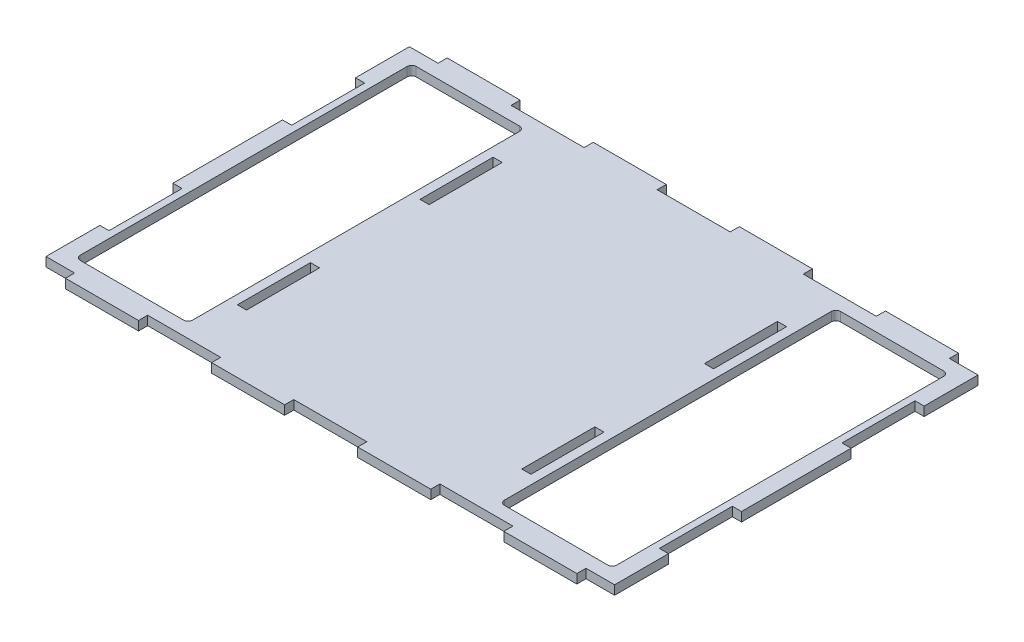
SolidWorks part; units mm, degrees
material "Acrylic (Medium-high impact)"
ref_plane "Front Plane" through (0, 0, 0) normal (0, 0, 1) x (1, 0, 0)
ref_plane "Top Plane" through (0, 0, 0) normal (0, 1, 0) x (1, 0, 0)
ref_plane "Right Plane" through (0, 0, 0) normal (1, 0, 0) x (0, 0, -1)
sketch "Sketch2" plane through (0, 0, 0) normal (0, 1, 0) x (1, 0, 0)
  line L0 (-147.5, 0) -> (147.5, 0) construction
  line L5 (-185, 195.2) -> (185, 195.2) construction
  line L6 (-197.7, -132.7) -> (197.7, -132.7)
  line L13 (110, 120) -> (185, 120)
  line L14 (110, 120) -> (110, -120)
  line L15 (110, -120) -> (185, -120)
  line L16 (185, 120) -> (185, -120)
  line L17 (110, 120) -> (185, -120) construction
  line L18 (110, -120) -> (185, 120) construction
  line L19 (-185, 120) -> (-110, 120)
  line L20 (-185, 120) -> (-185, -120)
  line L21 (-185, -120) -> (-110, -120)
  line L22 (-110, 120) -> (-110, -120)
  line L23 (-185, 120) -> (-110, -120) construction
  line L24 (-185, -120) -> (-110, 120) construction
  line L26 (-110, -37.5) -> (110, -37.5)
  line L27 (-110, -37.5) -> (-110, 37.5)
  line L28 (-110, 37.5) -> (110, 37.5)
  line L29 (110, -37.5) -> (110, 37.5)
  line L30 (-110, -37.5) -> (110, 37.5) construction
  line L31 (-110, 37.5) -> (110, -37.5) construction
  line L41 (-197.7, -132.7) -> (-197.7, 132.7)
  line L42 (-185, 132.7) -> (185, 132.7) construction
  line L43 (197.7, -132.7) -> (197.7, 132.7)
  line L44 (-197.7, -132.7) -> (197.7, 132.7) construction
  line L45 (-197.7, 132.7) -> (197.7, -132.7) construction
  line L47 (-197.7, 132.7) -> (-197.7, 257.7)
  line L48 (-197.7, 257.7) -> (-185, 257.7)
  line L49 (-185, 132.7) -> (-185, 257.7)
  line L51 (185, 132.7) -> (185, 257.7)
  line L52 (185, 257.7) -> (197.7, 257.7)
  line L53 (197.7, 132.7) -> (197.7, 257.7)
  line L54 (-185, 132.7) -> (185, 132.7)
  line L55 (223.1, 132.7) -> (223.1, 283.1)
  line L56 (159.6, 283.1) -> (223.1, 283.1)
  line L57 (159.6, 158.1) -> (159.6, 283.1)
  line L58 (-159.6, 158.1) -> (159.6, 158.1)
  line L59 (-159.6, 158.1) -> (-159.6, 283.1)
  line L60 (-223.1, 283.1) -> (-159.6, 283.1)
  line L61 (-223.1, 132.7) -> (-223.1, 283.1)
  line L62 (-223.1, -158.1) -> (-223.1, 132.7)
  line L63 (-223.1, -158.1) -> (223.1, -158.1)
  line L64 (223.1, -158.1) -> (223.1, 132.7)
  circle A0 centre (0, 308.1) radius 150
  point P2 (0, 0)
  point P13 (147.5, 0)
  point P18 (-147.5, 0)
  point P23 (0, 0)
  point P24 (0, 0)
  point P35 (0, 195.2)
  dimension "D1" = 300
  dimension "D2" = 75
  dimension "D3" = 240
  dimension "D4" = 75
  dimension "D5" = 220
  dimension "D6" = 12.7
  dimension "D7" = 12.7
  dimension "D8" = 12.7
  dimension "D9" = 125
  dimension "D10" = 25.4
sketch "Sketch5" plane through (0, 0, 0) normal (0, 1, 0) x (1, 0, 0)
  line L1 (197.7, -132.7) -> (-197.7, -132.7)
  line L2 (197.7, -132.7) -> (197.7, 132.7)
  line L3 (197.7, 132.7) -> (-197.7, 132.7)
  line L4 (-197.7, -132.7) -> (-197.7, 132.7)
extrude "Boss-Extrude3" add sketch "Sketch5" along normal blind 6.35
sketch "Sketch6" plane through (0, 6.35, 0) normal (0, 1, 0) x (1, 0, 0)
  line L0 (-185, 120) -> (-110, 120) construction
  line L1 (-185, 120) -> (-185, -120) construction
  line L2 (-185, -120) -> (-110, -120) construction
  line L3 (-110, 120) -> (-110, -120) construction
  line L4 (110, 120) -> (110, -120) construction
  line L5 (110, 120) -> (185, 120) construction
  line L6 (185, 120) -> (185, -120) construction
  line L7 (110, -120) -> (185, -120) construction
  line L8 (-185, 120) -> (-110, 120)
  line L9 (-185, 120) -> (-185, -120)
  line L10 (-185, -120) -> (-110, -120)
  line L11 (-110, 120) -> (-110, -120)
  line L12 (110, 120) -> (110, -120)
  line L13 (110, 120) -> (185, 120)
  line L14 (185, 120) -> (185, -120)
  line L15 (110, -120) -> (185, -120)
  line L16 (108.4125, 121.5875) -> (108.4125, -121.5875)
  line L17 (108.4125, -121.5875) -> (186.5875, -121.5875)
  line L18 (186.5875, 121.5875) -> (186.5875, -121.5875)
  line L19 (108.4125, 121.5875) -> (186.5875, 121.5875)
  line L20 (-108.4125, 121.5875) -> (-108.4125, -121.5875)
  line L21 (-186.5875, -121.5875) -> (-108.4125, -121.5875)
  line L22 (-186.5875, 121.5875) -> (-186.5875, -121.5875)
  line L23 (-186.5875, 121.5875) -> (-108.4125, 121.5875)
  dimension "D1" = 1.5875
extrude "Cut-Extrude1" cut sketch "Sketch6" against normal blind 6.35 contours L12 L15 L14 L13 | L19 L16 L17 L18 L15 L12 L13 L14 | L11 L8 L9 L10 | L23 L22 L21 L20 L8 L11 L10 L9
sketch "Sketch7" [suppressed] plane through (0, 6.35, 0) normal (0, 1, 0) x (1, 0, 0)
  arc A0 (191.675, -14.35) -> (191.043, -17.5242) centre (191.675, -16) ccw construction
  arc A1 (192.307, -14.4758) -> (191.675, -14.35) centre (191.675, -16) ccw construction
  arc A2 (191.675, -17.65) -> (192.307, -14.4758) centre (191.675, -16) ccw construction
  arc A3 (191.043, -17.5242) -> (191.675, -17.65) centre (191.675, -16) ccw construction
  arc A4 (191.675, 17.65) -> (191.043, 14.4758) centre (191.675, 16) ccw construction
  arc A5 (192.307, 17.5242) -> (191.675, 17.65) centre (191.675, 16) ccw construction
  arc A6 (191.675, 14.35) -> (192.307, 17.5242) centre (191.675, 16) ccw construction
  arc A7 (191.043, 14.4758) -> (191.675, 14.35) centre (191.675, 16) ccw construction
  arc A8 (103.325, -14.35) -> (102.693, -17.5242) centre (103.325, -16) ccw construction
  arc A9 (103.957, -14.4758) -> (103.325, -14.35) centre (103.325, -16) ccw construction
  arc A10 (103.325, -17.65) -> (103.957, -14.4758) centre (103.325, -16) ccw construction
  arc A11 (102.693, -17.5242) -> (103.325, -17.65) centre (103.325, -16) ccw construction
  arc A12 (103.325, 17.65) -> (102.693, 14.4758) centre (103.325, 16) ccw construction
  arc A13 (103.957, 17.5242) -> (103.325, 17.65) centre (103.325, 16) ccw construction
  arc A14 (103.325, 14.35) -> (103.957, 17.5242) centre (103.325, 16) ccw construction
  arc A15 (102.693, 14.4758) -> (103.325, 14.35) centre (103.325, 16) ccw construction
  arc A16 (-103.325, 17.65) -> (-103.957, 14.4758) centre (-103.325, 16) ccw construction
  arc A17 (-102.693, 17.5242) -> (-103.325, 17.65) centre (-103.325, 16) ccw construction
  arc A18 (-103.325, 14.35) -> (-102.693, 17.5242) centre (-103.325, 16) ccw construction
  arc A19 (-103.957, 14.4758) -> (-103.325, 14.35) centre (-103.325, 16) ccw construction
  arc A20 (-103.325, -14.35) -> (-103.957, -17.5242) centre (-103.325, -16) ccw construction
  arc A21 (-102.693, -14.4758) -> (-103.325, -14.35) centre (-103.325, -16) ccw construction
  arc A22 (-103.325, -17.65) -> (-102.693, -14.4758) centre (-103.325, -16) ccw construction
  arc A23 (-103.957, -17.5242) -> (-103.325, -17.65) centre (-103.325, -16) ccw construction
  arc A24 (-191.675, -14.35) -> (-192.307, -17.5242) centre (-191.675, -16) ccw construction
  arc A25 (-191.043, -14.4758) -> (-191.675, -14.35) centre (-191.675, -16) ccw construction
  arc A26 (-191.675, -17.65) -> (-191.043, -14.4758) centre (-191.675, -16) ccw construction
  arc A27 (-192.307, -17.5242) -> (-191.675, -17.65) centre (-191.675, -16) ccw construction
  arc A28 (-191.675, 14.35) -> (-191.043, 17.5242) centre (-191.675, 16) ccw construction
  arc A29 (-192.307, 14.4758) -> (-191.675, 14.35) centre (-191.675, 16) ccw construction
  arc A30 (-191.675, 17.65) -> (-192.307, 14.4758) centre (-191.675, 16) ccw construction
  arc A31 (-191.043, 17.5242) -> (-191.675, 17.65) centre (-191.675, 16) ccw construction
  circle A32 centre (-61.175, -10) radius 2.25 construction
  circle A33 centre (-61.175, 22) radius 2.25 construction
  circle A34 centre (61.175, 22) radius 2.25 construction
  circle A35 centre (61.175, -10) radius 2.25 construction
  arc A36 (191.675, -14.35) -> (191.043, -17.5242) centre (191.675, -16) ccw construction
  arc A37 (192.307, -14.4758) -> (191.675, -14.35) centre (191.675, -16) ccw construction
  arc A38 (191.675, -17.65) -> (192.307, -14.4758) centre (191.675, -16) ccw construction
  arc A39 (191.043, -17.5242) -> (191.675, -17.65) centre (191.675, -16) ccw construction
  arc A40 (191.675, 17.65) -> (191.043, 14.4758) centre (191.675, 16) ccw construction
  arc A41 (192.307, 17.5242) -> (191.675, 17.65) centre (191.675, 16) ccw construction
  arc A42 (191.675, 14.35) -> (192.307, 17.5242) centre (191.675, 16) ccw construction
  arc A43 (191.043, 14.4758) -> (191.675, 14.35) centre (191.675, 16) ccw construction
  arc A44 (103.325, -14.35) -> (102.693, -17.5242) centre (103.325, -16) ccw construction
  arc A45 (103.957, -14.4758) -> (103.325, -14.35) centre (103.325, -16) ccw construction
  arc A46 (103.325, -17.65) -> (103.957, -14.4758) centre (103.325, -16) ccw construction
  arc A47 (102.693, -17.5242) -> (103.325, -17.65) centre (103.325, -16) ccw construction
  arc A48 (103.325, 17.65) -> (102.693, 14.4758) centre (103.325, 16) ccw construction
  arc A49 (103.957, 17.5242) -> (103.325, 17.65) centre (103.325, 16) ccw construction
  arc A50 (103.325, 14.35) -> (103.957, 17.5242) centre (103.325, 16) ccw construction
  arc A51 (102.693, 14.4758) -> (103.325, 14.35) centre (103.325, 16) ccw construction
  arc A52 (-103.325, 17.65) -> (-103.957, 14.4758) centre (-103.325, 16) ccw construction
  arc A53 (-102.693, 17.5242) -> (-103.325, 17.65) centre (-103.325, 16) ccw construction
  arc A54 (-103.325, 14.35) -> (-102.693, 17.5242) centre (-103.325, 16) ccw construction
  arc A55 (-103.957, 14.4758) -> (-103.325, 14.35) centre (-103.325, 16) ccw construction
  arc A56 (-103.325, -14.35) -> (-103.957, -17.5242) centre (-103.325, -16) ccw construction
  arc A57 (-102.693, -14.4758) -> (-103.325, -14.35) centre (-103.325, -16) ccw construction
  arc A58 (-103.325, -17.65) -> (-102.693, -14.4758) centre (-103.325, -16) ccw construction
  arc A59 (-103.957, -17.5242) -> (-103.325, -17.65) centre (-103.325, -16) ccw construction
  arc A60 (-191.675, -14.35) -> (-192.307, -17.5242) centre (-191.675, -16) ccw construction
  arc A61 (-191.043, -14.4758) -> (-191.675, -14.35) centre (-191.675, -16) ccw construction
  arc A62 (-191.675, -17.65) -> (-191.043, -14.4758) centre (-191.675, -16) ccw construction
  arc A63 (-192.307, -17.5242) -> (-191.675, -17.65) centre (-191.675, -16) ccw construction
  arc A64 (-191.675, 14.35) -> (-191.043, 17.5242) centre (-191.675, 16) ccw construction
  arc A65 (-192.307, 14.4758) -> (-191.675, 14.35) centre (-191.675, 16) ccw construction
  arc A66 (-191.675, 17.65) -> (-192.307, 14.4758) centre (-191.675, 16) ccw construction
  arc A67 (-191.043, 17.5242) -> (-191.675, 17.65) centre (-191.675, 16) ccw construction
  circle A68 centre (-61.175, -10) radius 2.25 construction
  circle A69 centre (-61.175, 22) radius 2.25 construction
  circle A70 centre (61.175, 22) radius 2.25 construction
  circle A71 centre (61.175, -10) radius 2.25 construction
hole_wizard "Ø4.0mm Dowel Hole1" [suppressed] positions "Sketch8" profile "Sketch9" hole size "Ø4.0" standard "ANSI Metric"
sketch "Sketch8" [suppressed] plane through (0, 6.35, 0) normal (0, 1, 0) x (1, 0, 0)
  point P0 (191.675, -16)
  point P3 (191.675, 16)
  point P6 (103.325, -16)
  point P9 (103.325, 16)
  point P12 (-191.675, -16)
  point P15 (-191.675, 16)
  point P18 (-103.325, -16)
  point P21 (-103.325, 16)
  point P24 (-61.175, -10)
  point P27 (-61.175, 22)
  point P30 (61.175, 22)
  point P33 (61.175, -10)
sketch "Sketch9" plane through (191.675, 6.35, 16) normal (1, 0, 0) x (0, 0, 1)
  line L0 (0, 0) -> (0, 6.35)
  line L1 (0, 6.35) -> (2.25, 6.35)
  line L2 (2.25, 6.35) -> (2.25, 0)
  line L5 (2.25, 0) -> (0, 0)
  line L11 (0, -6.35) -> (0, 107.95) construction
  dimension "Thru Hole Dia." = 4.5
  dimension "Thru Hole Depth" = 6.35
sketch "Sketch10" plane through (0, 0, 0) normal (0, -1, 0) x (1, 0, 0)
  line L0 (-191.35, -126.35) -> (191.35, -126.35)
  line L1 (191.35, -126.35) -> (191.35, 126.35)
  line L2 (191.35, 126.35) -> (-191.35, 126.35)
  line L3 (-191.35, 126.35) -> (-191.35, -126.35)
  line L4 (197.7, -132.7) -> (197.7, 132.7)
  line L5 (197.7, 132.7) -> (-197.7, 132.7)
  line L6 (-197.7, 132.7) -> (-197.7, -132.7)
  line L7 (-197.7, -132.7) -> (197.7, -132.7)
  line L8 (197.7, -132.7) -> (197.7, 132.7)
  line L9 (197.7, 132.7) -> (-197.7, 132.7)
  line L10 (-197.7, 132.7) -> (-197.7, -132.7)
  line L11 (-197.7, -132.7) -> (197.7, -132.7)
  line L12 (102.0625, -126.35) -> (102.0625, 126.35)
  line L13 (-102.0625, -126.35) -> (-102.0625, 126.35)
  line L14 (108.4125, -126.35) -> (108.4125, 126.35)
  line L15 (-108.4125, -126.35) -> (-108.4125, 126.35)
  line L16 (108.4125, -121.5875) -> (108.4125, 121.5875) construction
  line L17 (-108.4125, -121.5875) -> (-108.4125, 121.5875) construction
  line L18 (95.7125, -126.35) -> (95.7125, 126.35)
  line L19 (-95.7125, -126.35) -> (-95.7125, 126.35)
  line L20 (197.7, 0) -> (-197.7, 0) construction
  line L21 (102.0625, -88.9) -> (95.7125, -88.9)
  line L22 (102.0625, -88.9) -> (102.0625, -38.1)
  line L23 (102.0625, -38.1) -> (95.7125, -38.1)
  line L24 (95.7125, -88.9) -> (95.7125, -38.1)
  line L25 (102.0625, 38.1) -> (95.7125, 38.1)
  line L26 (102.0625, 38.1) -> (102.0625, 88.9)
  line L27 (102.0625, 88.9) -> (95.7125, 88.9)
  line L28 (95.7125, 38.1) -> (95.7125, 88.9)
  line L29 (-102.0625, -88.9) -> (-95.7125, -88.9)
  line L30 (-102.0625, -88.9) -> (-102.0625, -38.1)
  line L31 (-102.0625, -38.1) -> (-95.7125, -38.1)
  line L32 (-95.7125, -88.9) -> (-95.7125, -38.1)
  line L33 (-95.7125, 88.9) -> (-102.0625, 88.9)
  line L34 (-95.7125, 88.9) -> (-95.7125, 38.1)
  line L35 (-95.7125, 38.1) -> (-102.0625, 38.1)
  line L36 (-102.0625, 88.9) -> (-102.0625, 38.1)
  line L37 (76.2, 126.35) -> (25.4, 126.35)
  line L38 (76.2, 126.35) -> (76.2, 132.7)
  line L39 (76.2, 132.7) -> (25.4, 132.7)
  line L40 (25.4, 126.35) -> (25.4, 132.7)
  line L41 (-25.4, 126.35) -> (-76.2, 126.35)
  line L42 (-25.4, 126.35) -> (-25.4, 132.7)
  line L43 (-25.4, 132.7) -> (-76.2, 132.7)
  line L44 (-76.2, 126.35) -> (-76.2, 132.7)
  line L45 (177.8, 126.35) -> (127, 126.35)
  line L46 (177.8, 126.35) -> (177.8, 132.7)
  line L47 (177.8, 132.7) -> (127, 132.7)
  line L48 (127, 126.35) -> (127, 132.7)
  line L49 (-127, 126.35) -> (-177.8, 126.35)
  line L50 (-127, 126.35) -> (-127, 132.7)
  line L51 (-127, 132.7) -> (-177.8, 132.7)
  line L52 (-177.8, 126.35) -> (-177.8, 132.7)
  line L53 (-127, -132.7) -> (-177.8, -132.7)
  line L54 (-177.8, -126.35) -> (-177.8, -132.7)
  line L55 (-127, -126.35) -> (-177.8, -126.35)
  line L56 (-127, -126.35) -> (-127, -132.7)
  line L57 (-25.4, -132.7) -> (-76.2, -132.7)
  line L58 (-76.2, -126.35) -> (-76.2, -132.7)
  line L59 (-25.4, -126.35) -> (-76.2, -126.35)
  line L60 (-25.4, -126.35) -> (-25.4, -132.7)
  line L61 (76.2, -132.7) -> (25.4, -132.7)
  line L62 (25.4, -126.35) -> (25.4, -132.7)
  line L63 (76.2, -126.35) -> (25.4, -126.35)
  line L64 (76.2, -126.35) -> (76.2, -132.7)
  line L65 (177.8, -132.7) -> (127, -132.7)
  line L66 (127, -126.35) -> (127, -132.7)
  line L67 (177.8, -126.35) -> (127, -126.35)
  line L68 (177.8, -126.35) -> (177.8, -132.7)
  line L69 (191.35, 126.35) -> (197.7, 126.35)
  line L70 (-191.35, 126.35) -> (-197.7, 126.35)
  line L71 (-191.35, -126.35) -> (-197.7, -126.35)
  line L72 (191.35, -126.35) -> (197.7, -126.35)
  line M31 (197.7, -132.7) -> (197.7, 132.7)
  line M32 (197.7, 132.7) -> (-197.7, 132.7)
  line M33 (-197.7, 132.7) -> (-197.7, -132.7)
  line M34 (-197.7, -132.7) -> (197.7, -132.7)
  dimension "D3" = 6.35
  dimension "D4" = 6.35
  dimension "D5" = 6.35
  dimension "D6" = 6.35
  dimension "D7" = 50.8
  dimension "D8" = 50.8
  dimension "D9" = 76.2
  dimension "D10" = 38.1
  dimension "D11" = 50.8
  dimension "D12" = 50.8
  dimension "D13" = 50.8
  dimension "D14" = 25.4
  dimension "D15" = 50.8
  dimension "D16" = 50.8
  dimension "D17" = 50.8
  dimension "D18" = 50.8
  dimension "D1" = 0
  dimension "D2" = 6.35
extrude "Cut-Extrude2" cut sketch "Sketch10" against normal blind 6.35 contours L12 L23 L18 L21 | L12 L27 L18 L25 | L35 L19 L33 L13 | L31 L13 L29 L19 | L2 L69 L8 L46 M32 | L2 L48 L38 M32 | L42 L2 L40 M32 | L50 L2 L44 M32 | L70 L2 L52 M32 M33 | L0 L71 L54 M33 M34 | L58 L0 L56 M34 | L62 L0 L60 M34 | L66 L0 L64 M34 | L72 L0 L68 M34 M31
sketch "Sketch11" plane through (197.7, 0, 0) normal (1, 0, 0) x (0, 0, -1)
  line L0 (-88.9, 0) -> (-38.1, 0) construction
  line L1 (-38.1, 0) -> (-38.1, 6.35) construction
  line L2 (-38.1, 6.35) -> (-88.9, 6.35) construction
  line L3 (-88.9, 6.35) -> (-88.9, 0) construction
  line L4 (38.1, 0) -> (88.9, 0) construction
  line L5 (88.9, 0) -> (88.9, 6.35) construction
  line L6 (88.9, 6.35) -> (38.1, 6.35) construction
  line L7 (38.1, 6.35) -> (38.1, 0) construction
  line L8 (-88.9, 0) -> (-38.1, 0)
  line L9 (-38.1, 0) -> (-38.1, 6.35)
  line L10 (-38.1, 6.35) -> (-88.9, 6.35)
  line L11 (-88.9, 6.35) -> (-88.9, 0)
  line L12 (38.1, 0) -> (88.9, 0)
  line L13 (88.9, 0) -> (88.9, 6.35)
  line L14 (88.9, 6.35) -> (38.1, 6.35)
  line L15 (38.1, 6.35) -> (38.1, 0)
extrude "Cut-Extrude3" cut sketch "Sketch11" against normal blind 6.35
mirror "Mirror1" about plane through (0, 0, 0) normal (1, 0, 0) of "Cut-Extrude3"
sketch "Sketch12" plane through (0, 0, 0) normal (0, -1, 0) x (1, 0, 0)
  line L0 (108.4125, -121.5875) -> (108.4125, 121.5875) construction
  line L1 (186.5875, -121.5875) -> (108.4125, -121.5875)
  line L2 (186.5875, -121.5875) -> (186.5875, -116.825)
  line L3 (186.5875, -116.825) -> (108.4125, -116.825)
  line L4 (108.4125, -121.5875) -> (108.4125, -116.825)
  line L5 (186.5875, -121.5875) -> (186.5875, 121.5875) construction
  line L6 (108.4125, 121.5875) -> (186.5875, 121.5875)
  line L7 (108.4125, 121.5875) -> (108.4125, 116.825)
  line L8 (108.4125, 116.825) -> (186.5875, 116.825)
  line L9 (186.5875, 121.5875) -> (186.5875, 116.825)
  line L10 (-186.5875, -121.5875) -> (-186.5875, 121.5875) construction
  line L11 (-108.4125, 121.5875) -> (-186.5875, 121.5875)
  line L12 (-108.4125, 121.5875) -> (-108.4125, 116.825)
  line L13 (-108.4125, 116.825) -> (-186.5875, 116.825)
  line L14 (-186.5875, 121.5875) -> (-186.5875, 116.825)
  line L15 (-108.4125, -121.5875) -> (-108.4125, 121.5875) construction
  line L16 (-186.5875, -121.5875) -> (-108.4125, -121.5875)
  line L17 (-186.5875, -121.5875) -> (-186.5875, -116.825)
  line L18 (-186.5875, -116.825) -> (-108.4125, -116.825)
  line L19 (-108.4125, -121.5875) -> (-108.4125, -116.825)
  dimension "D1" = 4.7625
extrude "Boss-Extrude4" add sketch "Sketch12" against normal up to surface (6.35 mm away) up to face at (98.8875, 6.35, 63.5)
fillet "Fillet1" radius 3.175 8 edges at (-186.5875, 3.175, 116.825) (-108.4125, 3.175, 116.825) (-186.5875, 3.175, -116.825) (-108.4125, 3.175, -116.825) (108.4125, 3.175, 116.825) (186.5875, 3.175, 116.825) (108.4125, 3.175, -116.825) (186.5875, 3.175, -116.825)
